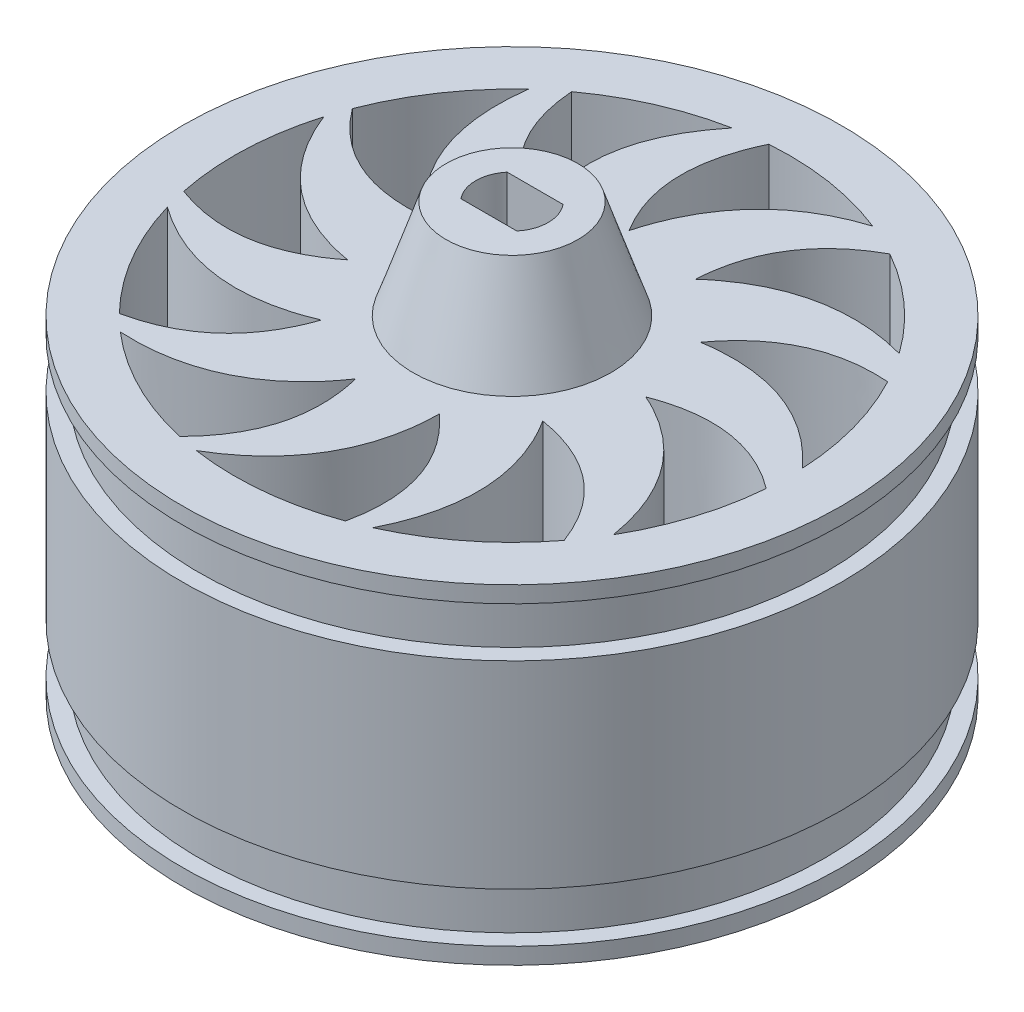
SolidWorks part; units mm, degrees
ref_plane "Front Plane" through (0, 0, 0) normal (0, 0, 1) x (1, 0, 0)
ref_plane "Top Plane" through (0, 0, 0) normal (0, 1, 0) x (1, 0, 0)
ref_plane "Right Plane" through (0, 0, 0) normal (1, 0, 0) x (0, 0, -1)
sketch "Sketch1" plane through (0, 0, 0) normal (0, 0, 1) x (1, 0, 0)
  line L0 (25.4, 5.08) -> (25.4, 20.32)
  line L1 (0, 0) -> (25.4, 0)
  line L2 (0, 0) -> (0, 25.4)
  line L3 (0, 12.7) -> (25.4, 12.7)
  line L4 (25.4, 0) -> (25.4, 1.27)
  line L5 (25.4, 5.08) -> (24.13, 5.08)
  line L7 (25.4, 1.27) -> (24.13, 1.27)
  line L8 (24.13, 5.08) -> (24.13, 1.27)
  line L9 (24.13, 20.32) -> (24.13, 24.13)
  line L10 (25.4, 24.13) -> (24.13, 24.13)
  line L11 (25.4, 20.32) -> (24.13, 20.32)
  line L12 (25.4, 25.4) -> (25.4, 24.13)
  line L13 (0, 25.4) -> (25.4, 25.4)
  line L14 (0, 25.4) -> (0, 33.02)
  line L15 (0, 33.02) -> (5.08, 33.02)
  line L16 (5.08, 33.02) -> (7.62, 25.4)
  dimension "D1" = 12.7
  dimension "D2" = 3.81
  dimension "D3" = 1.27
  dimension "D4" = 25.4
  dimension "D5" = 24.13
  dimension "D6" = 7.62
  dimension "D7" = 5.08
  dimension "D8" = 7.62
revolve "Revolve1" add sketch "Sketch1" angle 360 about L14
sketch "Sketch2" plane through (0, 0, 0) normal (0, -1, 0) x (1, 0, 0)
  circle A0 centre (0, 0) radius 3.175
  dimension "D1" = 6.35
extrude "Cut-Extrude1" cut sketch "Sketch2" against normal blind 6.35
sketch "Sketch3" plane through (0, 6.35, 0) normal (0, -1, 0) x (1, 0, 0)
  circle A0 centre (0, 0) radius 1.75
  dimension "D1" = 3.5
extrude "Cut-Extrude2" cut sketch "Sketch3" against normal up to surface (19.05 mm away) up to face at (25.4, 25.4, 0)
sketch "Sketch4" plane through (0, 33.02, 0) normal (0, 1, 0) x (1, 0, 0)
  line L0 (-2.1553, 1.778) -> (2.1553, 1.778)
  line L1 (2.4169, -1.4018) -> (2.1553, -1.778)
  line L2 (2.1553, -1.778) -> (-2.1553, -1.778)
  circle A0 centre (0, 0) radius 2.794
  dimension "D1" = 5.588
  dimension "D2" = 1.778
  dimension "D3" = 1.778
extrude "Cut-Extrude3" cut sketch "Sketch4" against normal up to surface (7.62 mm away) contours L1 A0 L0 L2 up to face at (25.4, 25.4, 0)
sketch "Sketch5" plane through (0, 25.4, 0) normal (0, 1, 0) x (1, 0, 0)
  circle A12 centre (0, 0) radius 21.4
  circle A13 centre (0, 0) radius 25.4 construction
  circle A14 centre (0, 0) radius 8.62
  circle A15 centre (0, 0) radius 7.62 construction
  spline S0 degree 2 poles (-1.1736, 10.1862) (-0.6653, 9.407) (0, 8.62) knots 0.882084 0.882084 0.882084 1 1 1
  spline S1 degree 2 poles (-5.3336, 6.7718) (-9.5953, 14.2137) (-4.055, 21.0123) knots 0 0 0 1 1 1
  spline S2 degree 2 poles (-1.1736, 10.1862) (-4.4041, 15.4046) (-1.5526, 21.3436) knots 0 0 0 1 1 1
  spline S3 degree 2 poles (12.651, 19.6853) (3.9523, 16.4523) (4.6603, 7.2516) knots 0 0 0 1 1 1
  spline S4 degree 2 poles (7.9189, 19.8809) (7.8742, 19.867) (6.0862, 19.3009) (2.5914, 17.1125) (0.1437, 13.798) (-0.9259, 11.1301) (-1.2846, 9.7653) (-1.4655, 8.9709) (-1.5526, 8.479) knots 0.182706 0.182706 0.182706 0.1875 0.375 0.625 0.8125 0.920381 0.952229 1 1 1
  spline S5 degree 2 poles (21.2854, 9.7207) (12.2197, 11.7038) (7.841, 3.5809) knots 0 0 0 1 1 1
  spline S6 degree 2 poles (17.4413, 12.4001) (17.2308, 12.4574) (16.4489, 12.65) (14.0782, 13.0626) (9.968, 12.7311) (6.2683, 10.9177) (4.0895, 9.043) (3.2606, 8.1279) (3.1642, 8.0182) knots 0.106508 0.106508 0.106508 0.128269 0.1875 0.375 0.625 0.8125 0.920381 0.934752 0.934752 0.934752
  spline S7 degree 2 poles (23.1618, -3.3302) (16.6074, 3.2394) (8.5323, -1.2268) knots 0 0 0 1 1 1
  spline S8 degree 2 poles (21.3765, 1.0022) (21.2305, 1.1642) (20.6768, 1.7489) (18.9055, 3.3777) (15.2686, 5.321) (11.1758, 5.7957) (8.3293, 5.3965) (7.1373, 5.0748) (6.9969, 5.0347) knots 0.106508 0.106508 0.106508 0.128269 0.1875 0.375 0.625 0.8125 0.920381 0.934752 0.934752 0.934752
  spline S9 degree 2 poles (17.6845, -15.3237) (15.7224, -6.2535) (6.5146, -5.6449) knots 0 0 0 1 1 1
  spline S10 degree 2 poles (18.5249, -10.7139) (18.4896, -10.4987) (18.34, -9.7075) (17.7304, -7.3796) (15.7215, -3.7785) (12.535, -1.1665) (9.9246, 0.0367) (8.7479, 0.4105) (8.6081, 0.4526) knots 0.106508 0.106508 0.106508 0.128269 0.1875 0.375 0.625 0.8125 0.920381 0.934752 0.934752 0.934752
  spline S11 degree 2 poles (6.5925, -22.4521) (9.8456, -13.761) (2.4285, -8.2708) knots 0 0 0 1 1 1
  spline S12 degree 2 poles (8.7861, -19.5132) (8.9023, -19.2834) (9.2615, -18.5197) (10.1327, -16.2765) (10.6168, -12.1816) (9.5672, -8.1972) (8.158, -5.692) (7.4147, -4.6866) (7.3163, -4.5581) knots 0.102615 0.102615 0.102615 0.128269 0.1875 0.375 0.625 0.8125 0.920381 0.936305 0.936305 0.936305
  spline S13 degree 2 poles (-6.5925, -22.4521) (0.8429, -16.8994) (-2.4285, -8.2708) knots 0 0 0 1 1 1
  spline S14 degree 2 poles (-3.1583, -21.1657) (-2.9363, -21.0352) (-2.2212, -20.5869) (-0.2755, -19.1708) (2.3456, -15.9877) (3.6167, -12.0684) (3.7856, -9.199) (3.7038, -7.9513) (3.6906, -7.79) knots 0.102615 0.102615 0.102615 0.128269 0.1875 0.375 0.625 0.8125 0.920381 0.936305 0.936305 0.936305
  spline S15 degree 2 poles (-17.6845, -15.3237) (-8.4274, -14.6724) (-6.5146, -5.6449) knots 0 0 0 1 1 1
  spline S16 degree 2 poles (-14.0127, -16.1742) (-13.7993, -16.1857) (-12.9987, -16.2098) (-10.5941, -16.1157) (-6.6451, -14.9291) (-3.4083, -12.3796) (-1.6714, -10.0894) (-0.9649, -8.8685) (-0.8114, -8.5817) knots 0.106944 0.106944 0.106944 0.128269 0.1875 0.375 0.625 0.8125 0.920381 0.952169 0.952169 0.952169
  spline S17 degree 2 poles (-23.1618, -3.3302) (-15.0221, -7.787) (-8.5323, -1.2268) knots 0 0 0 1 1 1
  spline S18 degree 2 poles (-20.5326, -6.0308) (-20.3593, -6.1559) (-19.6989, -6.6089) (-17.6251, -7.8298) (-13.6615, -8.9665) (-9.5602, -8.5717) (-6.8608, -7.5841) (-5.6064, -6.939) (-5.3223, -6.7807) knots 0.106944 0.106944 0.106944 0.128269 0.1875 0.375 0.625 0.8125 0.920381 0.952169 0.952169 0.952169
  spline S19 degree 2 poles (-21.2854, 9.7207) (-16.8473, 1.5707) (-7.841, 3.5809) knots 0 0 0 1 1 1
  spline S20 degree 2 poles (-20.5337, 6.0273) (-20.4555, 5.8284) (-20.1448, 5.0902) (-19.0603, 2.9421) (-16.3404, -0.1572) (-12.6767, -2.0424) (-9.872, -2.6709) (-8.4679, -2.8064) (-8.1433, -2.8269) knots 0.106944 0.106944 0.106944 0.128269 0.1875 0.375 0.625 0.8125 0.920381 0.952169 0.952169 0.952169
  spline S21 degree 2 poles (-12.651, 19.6853) (-13.3237, 10.4297) (-4.6603, 7.2516) knots 0 0 0 1 1 1
  spline S22 degree 2 poles (-14.4883, 15.7495) (-14.5564, 15.2325) (-14.6378, 14.1354) (-14.6494, 11.729) (-13.6374, 7.7316) (-11.2326, 4.386) (-9.1321, 2.6425) (-8.3535, 2.1267) knots 0.076851 0.076851 0.076851 0.128269 0.1875 0.375 0.625 0.8125 0.905523 0.905523 0.905523
  point P14 (-5.3223, 6.7718)
  point P65 (-7.1775, 13.5547)
  point P67 (0, 0)
  dimension "D2" = 1
  dimension "D1" = 4
extrude "Cut-Extrude4" cut sketch "Sketch5" against normal through all contours A12 S21 S1 | S4 A12 S2 | S6 A12 S3 | S8 A12 S5 | S10 A12 S7 | S12 A12 S9 | S14 A12 S11 | S16 A12 S13 | S18 A12 S15 | S20 A12 S17 | S22 A12 S19
